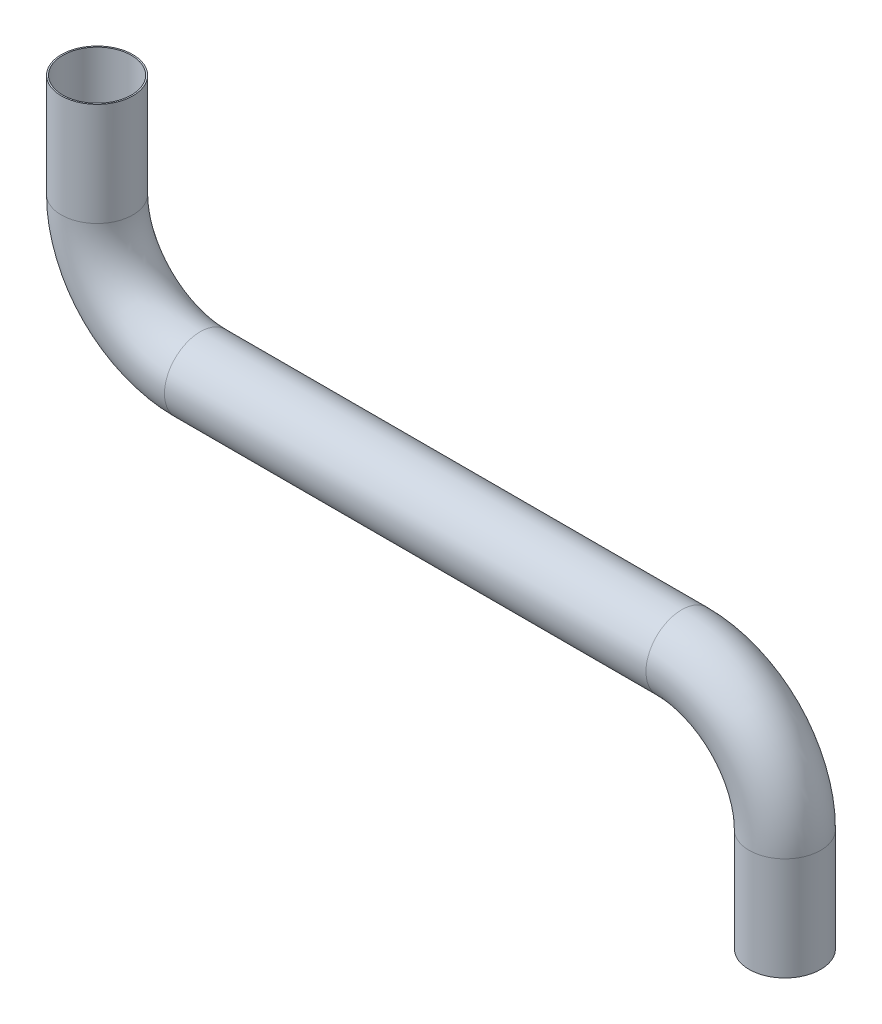
SolidWorks part; units mm, degrees
ref_plane "Front Plane" through (0, 0, 0) normal (0, 0, 1) x (1, 0, 0)
ref_plane "Top Plane" through (0, 0, 0) normal (0, 1, 0) x (1, 0, 0)
ref_plane "Right Plane" through (0, 0, 0) normal (1, 0, 0) x (0, 0, -1)
sketch "Sketch1" plane through (0, 0, 0) normal (0, 1, 0) x (1, 0, 0)
  circle A0 centre (0, 0) radius 25
  dimension "D1" = 50
sketch "Sketch2" plane through (0, 0, 0) normal (0, 0, 1) x (1, 0, 0)
  line L0 (0, 0) -> (0, -75)
  line L1 (75, -150) -> (425, -150)
  line L2 (500, -225) -> (500, -300)
  arc A0 (425, -150) -> (500, -225) centre (425, -225) cw
  arc A1 (0, -75) -> (75, -150) centre (75, -75) ccw
  point P7 (500, -150)
  point P10 (0, -150)
  dimension "D4" = 75
  dimension "D1" = 150
  dimension "D2" = 500
  dimension "D3" = 150
sweep "Sweep-Thin1" add profiles "Sketch1" path "Sketch2" parameters "D1"=1
